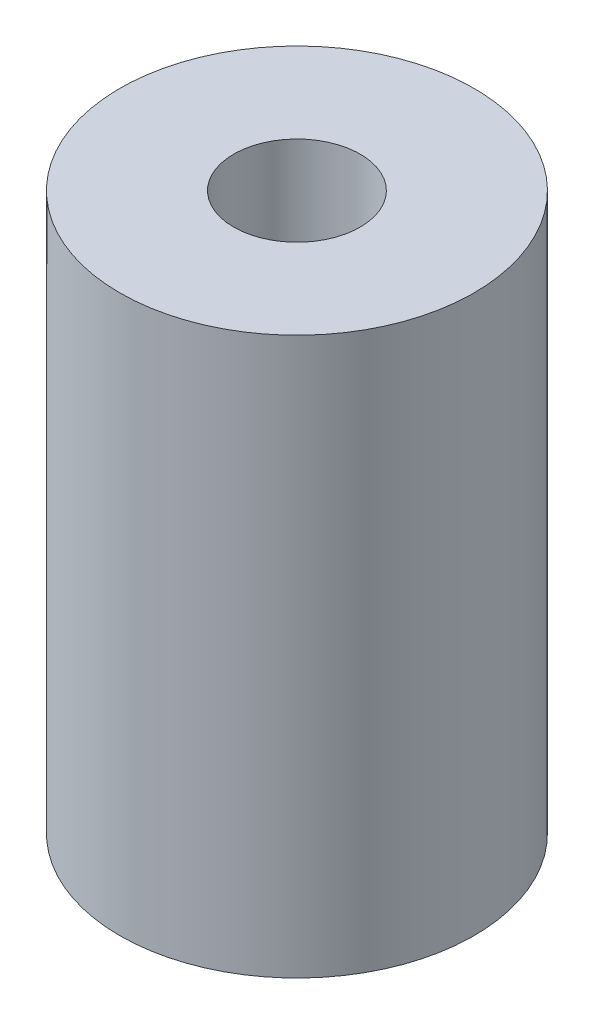
SolidWorks part; units mm, degrees
ref_plane "前视基准面" through (0, 0, 0) normal (0, 0, 1) x (1, 0, 0)
ref_plane "上视基准面" through (0, 0, 0) normal (0, 1, 0) x (1, 0, 0)
ref_plane "右视基准面" through (0, 0, 0) normal (1, 0, 0) x (0, 0, -1)
sketch "草图1" plane through (0, 0, 0) normal (0, 1, 0) x (1, 0, 0)
  circle A0 centre (0, 0) radius 7
  dimension "D1" = 14
extrude "凸台-拉伸1" add sketch "草图1" along normal blind 22
sketch "草图2" plane through (0, 22, 0) normal (0, 1, 0) x (1, 0, 0)
  circle A0 centre (0, 0) radius 2.5
  dimension "D1" = 5
extrude "切除-拉伸2" cut sketch "草图2" against normal blind 22
sketch "草图3" plane through (0, 0, 0) normal (0, -1, 0) x (1, 0, 0)
  circle A0 centre (0, 0) radius 3
  dimension "D1" = 6
extrude "切除-拉伸3" cut sketch "草图3" against normal blind 11
